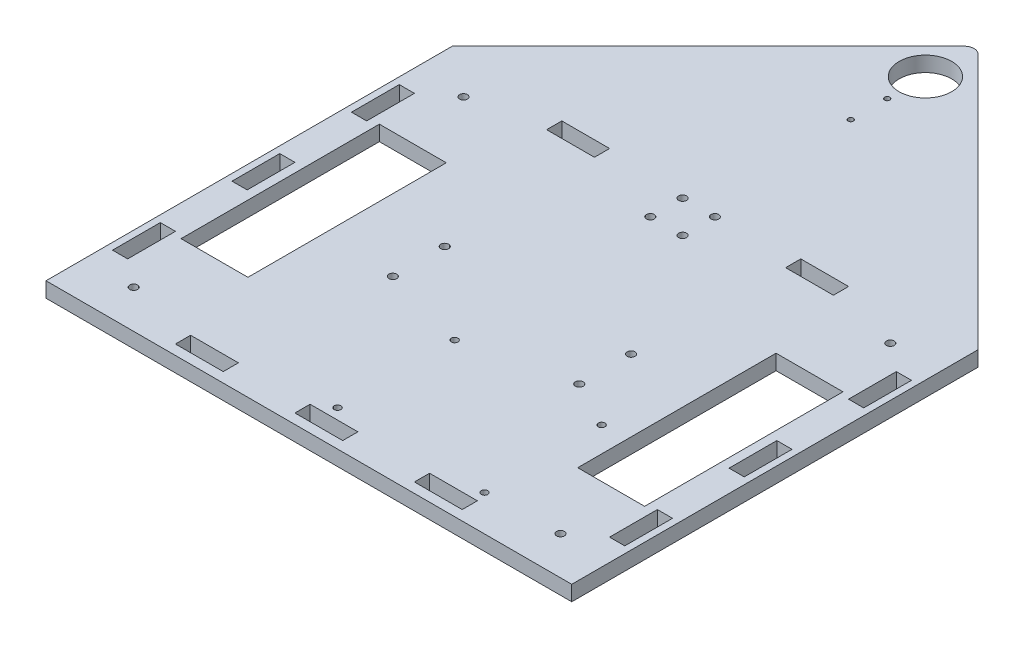
SolidWorks part; units mm, degrees
ref_plane "Front Plane" through (0, 0, 0) normal (0, 0, 1) x (1, 0, 0)
ref_plane "Top Plane" through (0, 0, 0) normal (0, 1, 0) x (1, 0, 0)
ref_plane "Right Plane" through (0, 0, 0) normal (1, 0, 0) x (0, 0, -1)
sketch "Sketch1" plane through (0, 0, 0) normal (0, 1, 0) x (1, 0, 0)
  line L0 (-110, 85) -> (-2.8284, 192.1716)
  line L1 (-110, 85) -> (110, 85) construction
  line L2 (-110, 85) -> (-110, -85)
  line L3 (-110, -85) -> (110, -85)
  line L4 (110, 85) -> (110, -85)
  line L5 (-110, 85) -> (110, -85) construction
  line L6 (-110, -85) -> (110, 85) construction
  line L7 (2.8284, 192.1716) -> (110, 85)
  line L8 (0, 85) -> (0, -85) construction
  line L9 (-97, 41.5) -> (-69, 41.5)
  line L10 (-97, 41.5) -> (-97, -41.5)
  line L11 (-97, -41.5) -> (-69, -41.5)
  line L12 (-69, 41.5) -> (-69, -41.5)
  line L13 (-97, 41.5) -> (-69, -41.5) construction
  line L14 (-97, -41.5) -> (-69, 41.5) construction
  line L15 (-110, 0) -> (110, 0) construction
  line L16 (-107.175, 60) -> (-100.825, 60)
  line L17 (-107.175, 10) -> (-100.825, 10)
  line L18 (-107.175, 10) -> (-107.175, -10)
  line L19 (-107.175, -10) -> (-100.825, -10)
  line L20 (-100.825, 10) -> (-100.825, -10)
  line L21 (-107.175, 10) -> (-100.825, -10) construction
  line L22 (-107.175, -10) -> (-100.825, 10) construction
  line L23 (-107.175, 60) -> (-107.175, 40)
  line L24 (-107.175, 40) -> (-100.825, 40)
  line L25 (-100.825, 60) -> (-100.825, 40)
  line L26 (-107.175, 60) -> (-100.825, 40) construction
  line L27 (-107.175, 40) -> (-100.825, 60) construction
  line L28 (-107.175, -40) -> (-100.825, -40)
  line L29 (-107.175, -40) -> (-107.175, -60)
  line L30 (-107.175, -60) -> (-100.825, -60)
  line L31 (-100.825, -40) -> (-100.825, -60)
  line L32 (-107.175, -40) -> (-100.825, -60) construction
  line L33 (-107.175, -60) -> (-100.825, -40) construction
  line L34 (40, -74.4921) -> (60, -74.4921)
  line L35 (-10, -74.4921) -> (10, -74.4921)
  line L36 (-10, -74.4921) -> (-10, -80.8421)
  line L37 (-10, -80.8421) -> (10, -80.8421)
  line L38 (10, -74.4921) -> (10, -80.8421)
  line L39 (-10, -74.4921) -> (10, -80.8421) construction
  line L40 (-10, -80.8421) -> (10, -74.4921) construction
  line L41 (40, -74.4921) -> (40, -80.8421)
  line L42 (40, -80.8421) -> (60, -80.8421)
  line L43 (60, -74.4921) -> (60, -80.8421)
  line L44 (40, -74.4921) -> (60, -80.8421) construction
  line L45 (40, -80.8421) -> (60, -74.4921) construction
  line L46 (-60, -74.4921) -> (-40, -74.4921)
  line L47 (-60, -74.4921) -> (-60, -80.8421)
  line L48 (-60, -80.8421) -> (-40, -80.8421)
  line L49 (-40, -74.4921) -> (-40, -80.8421)
  line L50 (-60, -74.4921) -> (-40, -80.8421) construction
  line L51 (-60, -80.8421) -> (-40, -74.4921) construction
  line L52 (107.175, -60) -> (100.825, -40) construction
  line L53 (107.175, -40) -> (100.825, -60) construction
  line L54 (107.175, 40) -> (100.825, 60) construction
  line L55 (107.175, 60) -> (100.825, 40) construction
  line L56 (107.175, -10) -> (100.825, 10) construction
  line L57 (107.175, 10) -> (100.825, -10) construction
  line L58 (100.825, -40) -> (100.825, -60)
  line L59 (107.175, -60) -> (100.825, -60)
  line L60 (107.175, -40) -> (107.175, -60)
  line L61 (107.175, -40) -> (100.825, -40)
  line L62 (100.825, 60) -> (100.825, 40)
  line L63 (107.175, 40) -> (100.825, 40)
  line L64 (107.175, 60) -> (107.175, 40)
  line L65 (100.825, 10) -> (100.825, -10)
  line L66 (107.175, -10) -> (100.825, -10)
  line L67 (107.175, 10) -> (107.175, -10)
  line L68 (107.175, 10) -> (100.825, 10)
  line L69 (107.175, 60) -> (100.825, 60)
  line L70 (-60, 80.8421) -> (-40, 74.4921) construction
  line L71 (-60, 74.4921) -> (-40, 80.8421) construction
  line L72 (40, 80.8421) -> (60, 74.4921) construction
  line L73 (40, 74.4921) -> (60, 80.8421) construction
  line L76 (-40, 74.4921) -> (-40, 80.8421)
  line L77 (-60, 80.8421) -> (-40, 80.8421)
  line L78 (-60, 74.4921) -> (-60, 80.8421)
  line L79 (-60, 74.4921) -> (-40, 74.4921)
  line L80 (60, 74.4921) -> (60, 80.8421)
  line L81 (40, 80.8421) -> (60, 80.8421)
  line L82 (40, 74.4921) -> (40, 80.8421)
  line L87 (40, 74.4921) -> (60, 74.4921)
  line L88 (97, -41.5) -> (69, 41.5) construction
  line L89 (97, 41.5) -> (69, -41.5) construction
  line L90 (69, 41.5) -> (69, -41.5)
  line L91 (97, -41.5) -> (69, -41.5)
  line L92 (97, 41.5) -> (97, -41.5)
  line L93 (97, 41.5) -> (69, 41.5)
  line L94 (-3, -21) -> (-3, -70) construction
  line L95 (-26.5, -21) -> (58.5, -21) construction
  line L96 (-26.5, -21) -> (-26.5, -70) construction
  line L97 (-26.5, -70) -> (58.5, -70) construction
  line L98 (58.5, -21) -> (58.5, -70) construction
  line L99 (-26.5, -21) -> (58.5, -70) construction
  line L100 (-26.5, -70) -> (58.5, -21) construction
  line L102 (-6.75, 78.125) -> (6.75, 78.125) construction
  line L103 (-6.75, 78.125) -> (-6.75, 64.625) construction
  line L104 (-6.75, 64.625) -> (6.75, 64.625) construction
  line L105 (6.75, 78.125) -> (6.75, 64.625) construction
  line L106 (-6.75, 78.125) -> (6.75, 64.625) construction
  line L107 (-6.75, 64.625) -> (6.75, 78.125) construction
  circle A0 centre (-39, 10.85) radius 1.65
  circle A1 centre (-39, -10.85) radius 1.65
  circle A2 centre (-89.2941, -69) radius 1.65
  circle A3 centre (89.2941, -69) radius 1.65
  circle A4 centre (-89.2941, 69) radius 1.65
  circle A5 centre (89.2941, 69) radius 1.65
  circle A6 centre (39, -10.85) radius 1.65
  circle A7 centre (39, 10.85) radius 1.65
  circle A8 centre (0, 157) radius 1.1
  circle A9 centre (0, 141.75) radius 1.1
  circle A10 centre (-3, -21) radius 1.4
  circle A11 centre (-3, -70) radius 1.4
  circle A12 centre (58.5, -70) radius 1.4
  circle A13 centre (58.5, -21) radius 1.4
  circle A14 centre (-6.75, 78.125) radius 1.65
  circle A15 centre (6.75, 78.125) radius 1.65
  circle A16 centre (6.75, 64.625) radius 1.65
  circle A17 centre (-6.75, 64.625) radius 1.65
  circle A18 centre (0, 173) radius 11
  arc A19 (-2.8284, 192.1716) -> (2.8284, 192.1716) centre (0, 189.3431) cw
  point P0 (0, 0)
  point P6 (-83, 0)
  point P20 (-104, 0)
  point P25 (0, -77.6671)
  point P27 (-104, 50)
  point P32 (-104, -50)
  point P41 (50, -77.6671)
  point P46 (-50, -77.6671)
  point P62 (104, -50)
  point P63 (104, 50)
  point P64 (104, 0)
  point P75 (0, 0)
  point P76 (0, 0)
  point P77 (-50, 77.6671)
  point P78 (50, 77.6671)
  point P96 (83, 0)
  point P101 (16, -45.5)
  point P112 (0, 71.375)
  point P122 (-0.3629, 192.6313)
  point P123 (0, 195)
  dimension "D6" = 3.3
  dimension "D16" = 3.3
  dimension "D20" = 2.2
  dimension "D25" = 2.8
  dimension "D28" = 3.3
  dimension "D33" = 22
  dimension "D29" = 4
  dimension "D1" = 83
  dimension "D2" = 28
  dimension "D3" = 170
  dimension "D4" = 39
  dimension "D5" = 10.85
  dimension "D7" = 44
  dimension "D8" = 220
  dimension "D9" = 6.35
  dimension "D10" = 20
  dimension "D11" = 6
  dimension "D12" = 2
  dimension "D17" = 16
  dimension "D18" = 110
  dimension "D19" = 15.25
  dimension "D21" = 38
  dimension "D22" = 85
  dimension "D23" = 49
  dimension "D24" = 23.5
  dimension "D26" = 13.5
  dimension "D27" = 22
  dimension "D31" = 16
  dimension "D32" = 15
  dimension "D13" = 2
  dimension "D14" = 2
  dimension "D15" = 2
extrude "Boss-Extrude1" add sketch "Sketch1" along normal blind 6.35
